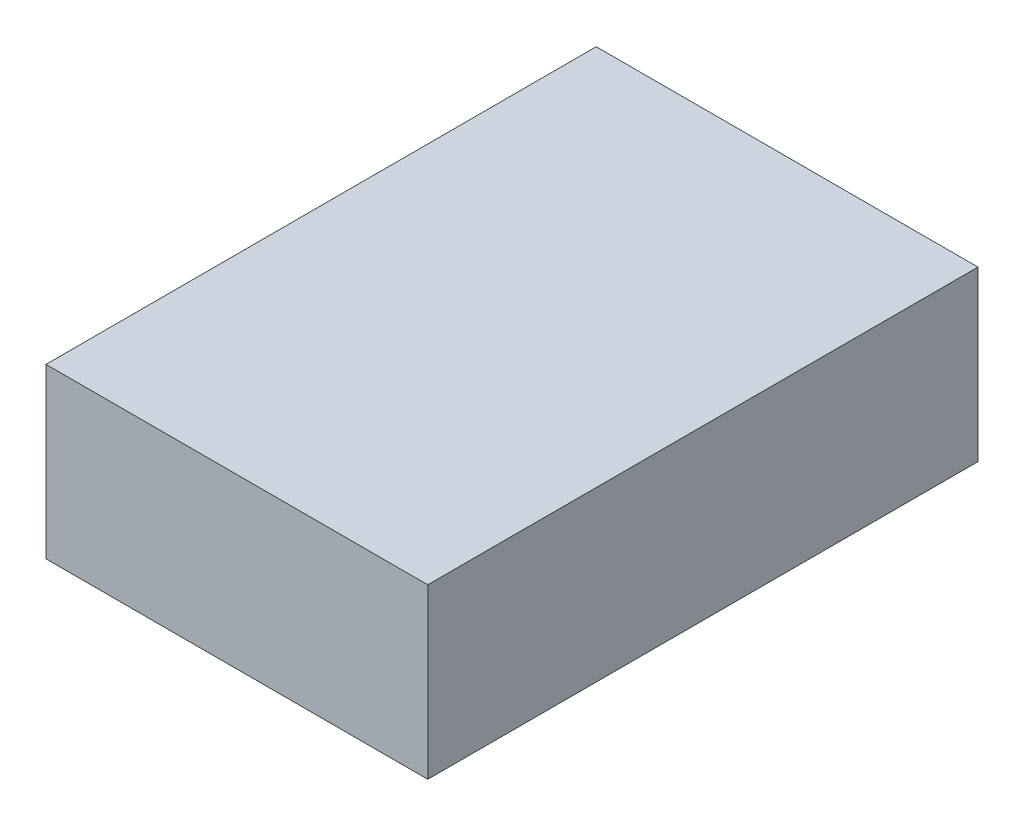
SolidWorks part; units mm, degrees
ref_plane "Front Plane" through (0, 0, 0) normal (0, 0, 1) x (1, 0, 0)
ref_plane "Top Plane" through (0, 0, 0) normal (0, 1, 0) x (1, 0, 0)
ref_plane "Right Plane" through (0, 0, 0) normal (1, 0, 0) x (0, 0, -1)
sketch "Sketch1" plane through (0, 0, 0) normal (0, 0, 1) x (1, 0, 0)
  line L1 (0, 0) -> (16.9983, 0)
  line L2 (0, 0) -> (0, 7.5)
  line L3 (0, 7.5) -> (16.9983, 7.5)
  line L4 (16.9983, 0) -> (16.9983, 7.5)
  dimension "D1" = 7.5
  dimension "17.4mm" = 16.9983
extrude "Boss-Extrude1" add sketch "Sketch1" along normal blind 24.5
